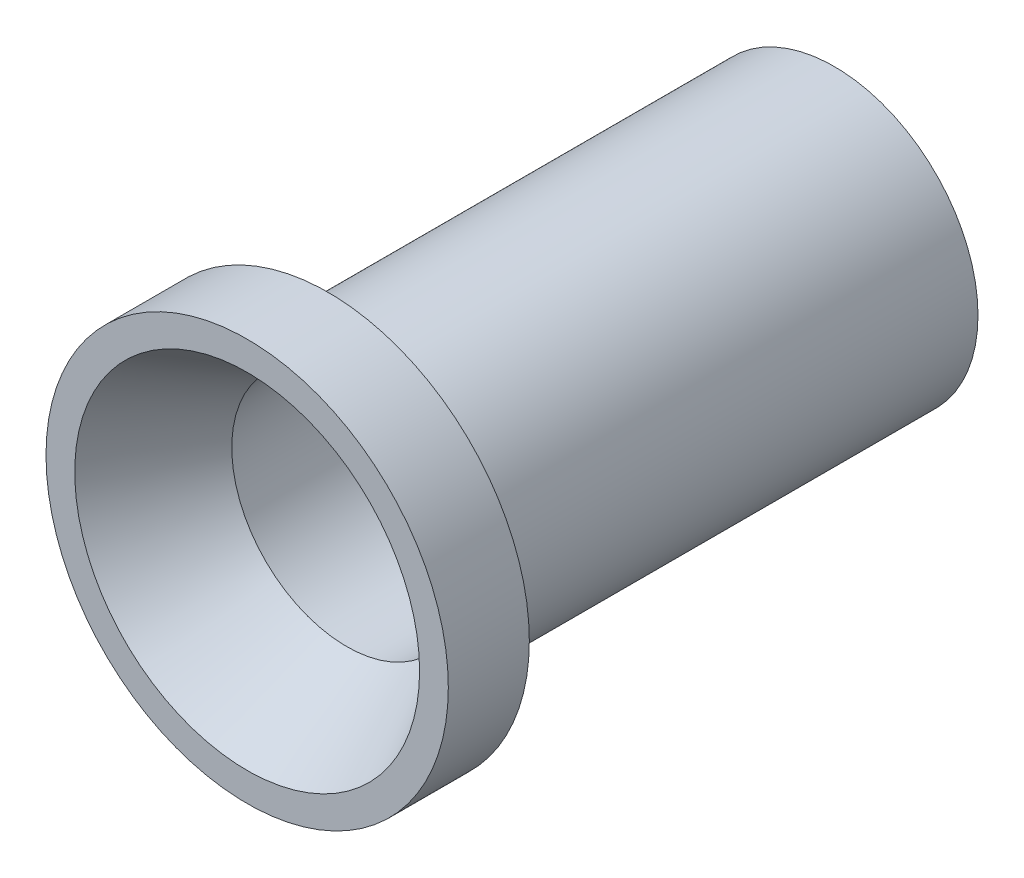
SolidWorks part; units mm, degrees
other "Папка сварных швов"
material "Сталь 12Х18Н9 ГОСТ 5632-72"
ref_plane "Front" through (0, 0, 0) normal (0, 0, 1) x (1, 0, 0)
ref_plane "Top" through (0, 0, 0) normal (0, 1, 0) x (1, 0, 0)
ref_plane "Right" through (0, 0, 0) normal (1, 0, 0) x (0, 0, -1)
sketch "Sketch1" plane through (0, 0, 0) normal (1, 0, 0) x (0, 0, -1)
  line L3 (16.4974, 25) -> (100, 25)
  line L4 (100, 25) -> (100, 20)
  line L6 (-2.1578, 30) -> (-2.1578, 35)
  line L7 (15.1627, 20) -> (100, 20)
  line L8 (0, 0) -> (8.808, 0) construction
  line L9 (0, 0) -> (0, 6.1121) construction
  line L10 (-2.1578, 30) -> (15.1627, 20)
  line L11 (-2.1578, 35) -> (11.9365, 35)
  line L13 (16.4974, 25) -> (11.9365, 27.6332)
  line L14 (11.9365, 35) -> (11.9365, 27.6332)
  dimension "D1" = 50
  dimension "D2" = 5
  dimension "D3" = 15
  dimension "D4" = 30
  dimension "D5" = 5
  dimension "D9" = 100
revolve "Revolve1" add sketch "Sketch1" angle 360 about L8
